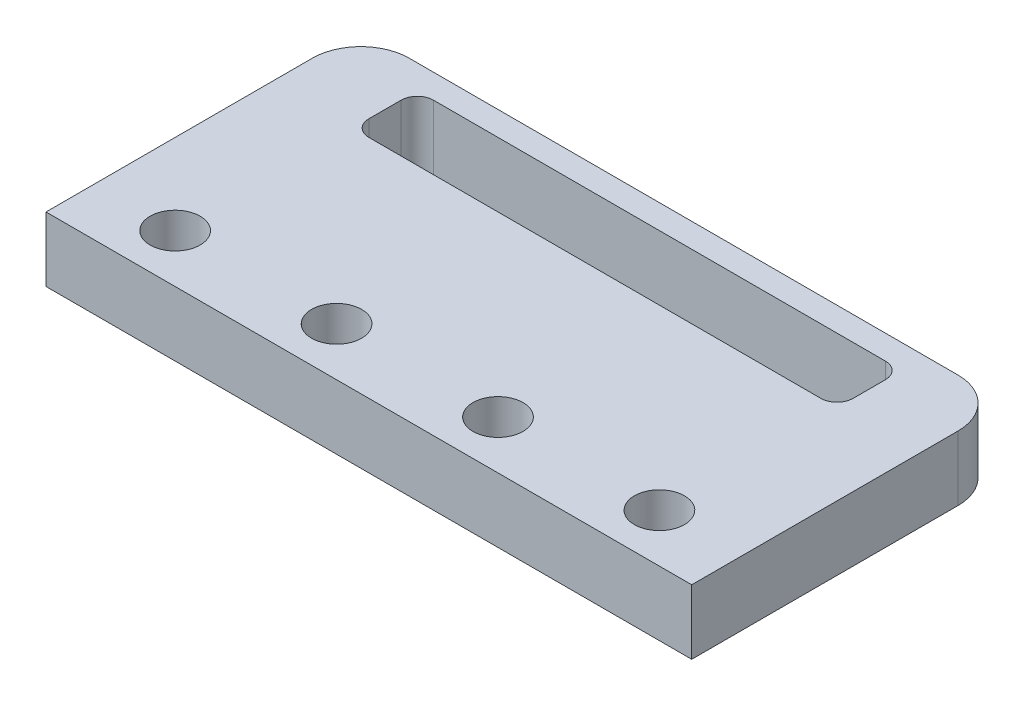
SolidWorks part; units mm, degrees
material "VMA 碳纤维"
ref_plane "前视基准面" through (0, 0, 0) normal (0, 0, 1) x (1, 0, 0)
ref_plane "上视基准面" through (0, 0, 0) normal (0, 1, 0) x (1, 0, 0)
ref_plane "右视基准面" through (0, 0, 0) normal (1, 0, 0) x (0, 0, -1)
other "Configuration Table"
sketch "草图1" plane through (0, 0, 0) normal (0, 1, 0) x (1, 0, 0)
  line L0 (0, 0) -> (0, -6.75) construction
  line L1 (-20, -9.75) -> (20, -9.75)
  line L2 (-20, -9.75) -> (-20, 9.75)
  line L3 (-20, 9.75) -> (20, 9.75)
  line L4 (20, -9.75) -> (20, 9.75)
  line L5 (-20, -9.75) -> (20, 9.75) construction
  line L6 (-20, 9.75) -> (20, -9.75) construction
  line L7 (0, -6.75) -> (-5, -6.75) construction
  line L8 (-5, -6.75) -> (-15, -6.75) construction
  line L9 (0, -24.7027) -> (0, 0) construction
  circle A0 centre (-15, -6.75) radius 1.55
  circle A1 centre (-5, -6.75) radius 1.55
  circle A2 centre (15, -6.75) radius 1.55
  circle A3 centre (5, -6.75) radius 1.55
  point P0 (0, 0)
  dimension "D5" = 3.1
  dimension "D1" = 40
  dimension "D2" = 19.5
  dimension "D3" = 10
  dimension "D4" = 5
  dimension "D6" = 3
extrude "凸台-拉伸1" add sketch "草图1" along normal blind 4
sketch "草图2" plane through (0, 4, 0) normal (0, 1, 0) x (1, 0, 0)
  line L0 (0, 0) -> (0, 6.25) construction
  line L1 (-14, 4.25) -> (14, 4.25)
  line L2 (-15, 5.25) -> (-15, 7.25)
  line L3 (-14, 8.25) -> (14, 8.25)
  line L4 (15, 5.25) -> (15, 7.25)
  line L5 (-15, 4.25) -> (15, 8.25) construction
  line L6 (-15, 8.25) -> (15, 4.25) construction
  line L7 (20, 9.75) -> (-20, 9.75) construction
  arc A0 (14, 4.25) -> (15, 5.25) centre (14, 5.25) ccw
  arc A1 (-15, 7.25) -> (-14, 8.25) centre (-14, 7.25) cw
  arc A2 (-14, 4.25) -> (-15, 5.25) centre (-14, 5.25) cw
  arc A3 (14, 8.25) -> (15, 7.25) centre (14, 7.25) cw
  point P0 (0, 6.25)
  dimension "D4" = 1
  dimension "D1" = 30
  dimension "D2" = 4
  dimension "D3" = 1.5
extrude "切除-拉伸1" cut sketch "草图2" against normal blind 4
fillet "圆角1" radius 3 2 edges at (20, 2, -9.75) (-20, 2, -9.75)
